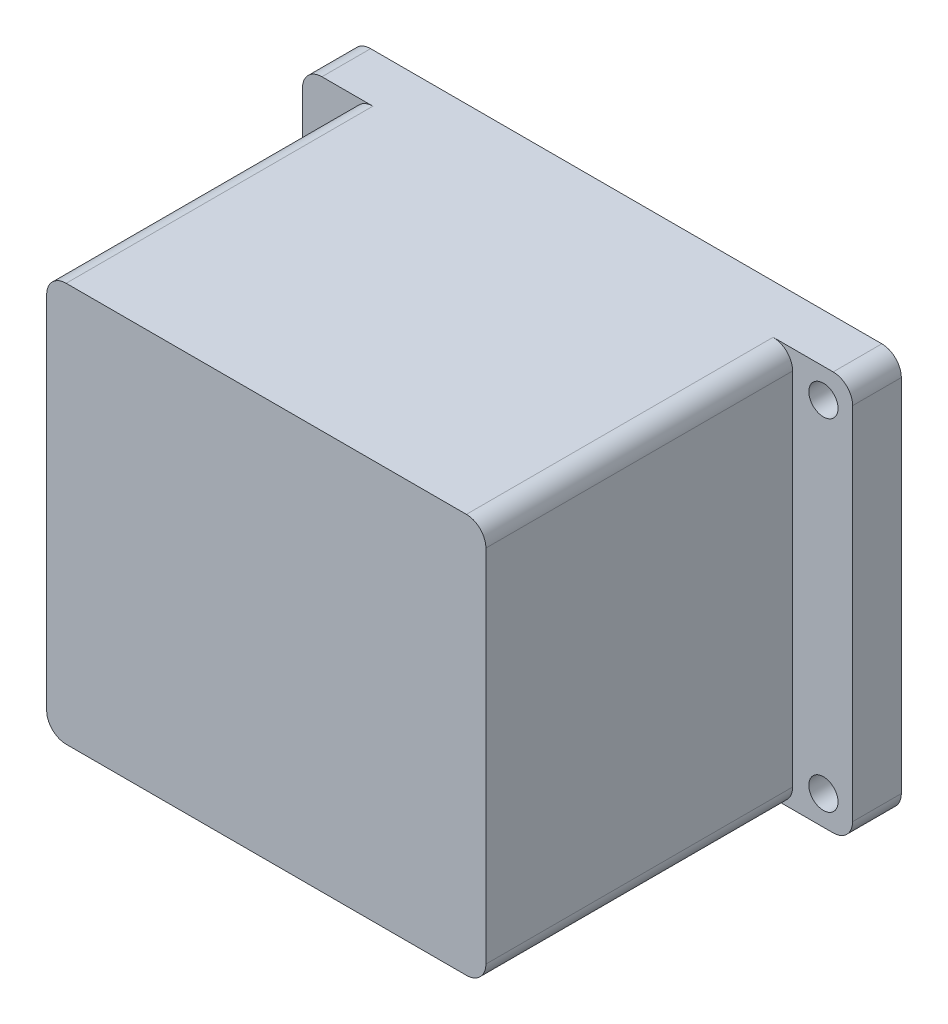
SolidWorks part; units mm, degrees
ref_plane "前视基准面" through (0, 0, 0) normal (0, 0, 1) x (1, 0, 0)
ref_plane "上视基准面" through (0, 0, 0) normal (0, 1, 0) x (1, 0, 0)
ref_plane "右视基准面" through (0, 0, 0) normal (1, 0, 0) x (0, 0, -1)
sketch "草图1" plane through (0, 0, 0) normal (0, 0, 1) x (1, 0, 0)
  line L0 (2.8, 41) -> (2.8, 0) construction
  line L1 (0, 0) -> (56.5, 0)
  line L2 (0, 0) -> (0, 41)
  line L3 (0, 41) -> (56.5, 41)
  line L4 (56.5, 0) -> (56.5, 41)
  line L5 (53.5, 41) -> (53.5, 0) construction
  circle A0 centre (2.8, 20.5) radius 1.5
  circle A1 centre (53.5, 38) radius 1.5
  circle A2 centre (53.5, 3) radius 1.5
  point P7 (2.8, 20.5)
  dimension "D3" = 3
  dimension "D4" = 2.8
  dimension "D6" = 3
  dimension "D7" = 3
  dimension "D1" = 56.5
  dimension "D2" = 41
  dimension "D5" = 3
  dimension "D8" = 3
  dimension "D9" = 3
extrude "凸台-拉伸1" add sketch "草图1" along normal blind 5
fillet "圆角1" radius 2 4 edges at (56.5, 41, 2.5) (0, 41, 2.5) (0, 0, 2.5) (56.5, 0, 2.5)
sketch "草图2" plane through (0, 0, 5) normal (0, 0, 1) x (1, 0, 0)
  line L0 (2, 0) -> (54.5, 0) construction
  line L1 (50.3353, 0) -> (5.2319, 0)
  line L2 (50.3353, 0) -> (50.3353, 41)
  line L3 (50.3353, 41) -> (5.2319, 41)
  line L4 (5.2319, 0) -> (5.2319, 41)
  line L5 (54.5, 41) -> (2, 41) construction
extrude "凸台-拉伸2" add sketch "草图2" along normal blind 31.5
fillet "圆角2" radius 2 4 edges at (5.2319, 0, 20.75) (50.3353, 0, 20.75) (50.3353, 41, 20.75) (5.2319, 41, 20.75)
